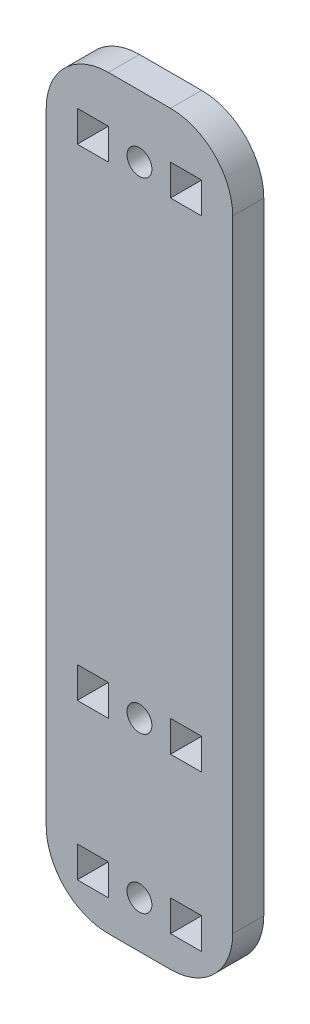
SolidWorks part; units mm, degrees
ref_plane "Plan de face" through (0, 0, 0) normal (0, 0, 1) x (1, 0, 0)
ref_plane "Plan de dessus" through (0, 0, 0) normal (0, 1, 0) x (1, 0, 0)
ref_plane "Plan de droite" through (0, 0, 0) normal (1, 0, 0) x (0, 0, -1)
sketch "Esquisse1" plane through (0, 0, 0) normal (0, 0, 1) x (1, 0, 0)
  line L0 (0, -120) -> (0, 0)
  line L1 (0, -120) -> (-30, -120)
  line L2 (0, 0) -> (-30, 0)
  line L3 (-20, -7.5) -> (-25, -7.5)
  line L4 (-5, -110) -> (-10, -110)
  line L5 (-5, -110) -> (-5, -115)
  line L6 (-5, -115) -> (-10, -115)
  line L7 (-10, -110) -> (-10, -115)
  line L8 (-20, -110) -> (-25, -110)
  line L9 (-20, -110) -> (-20, -115)
  line L10 (-20, -115) -> (-25, -115)
  line L11 (-25, -110) -> (-25, -115)
  line L12 (-20, -85) -> (-25, -85)
  line L13 (-20, -85) -> (-20, -90)
  line L14 (-20, -90) -> (-25, -90)
  line L15 (-25, -85) -> (-25, -90)
  line L16 (-5, -85) -> (-10, -85)
  line L17 (-5, -85) -> (-5, -90)
  line L18 (-30, -120) -> (-30, 0)
  line L19 (-20, -7.5) -> (-20, -12.5)
  line L20 (-20, -12.5) -> (-25, -12.5)
  line L21 (-25, -7.5) -> (-25, -12.5)
  line L22 (-5, -90) -> (-10, -90)
  line L23 (-5, -7.5) -> (-10, -7.5)
  line L24 (-5, -7.5) -> (-5, -12.5)
  line L25 (-5, -12.5) -> (-10, -12.5)
  line L26 (-10, -7.5) -> (-10, -12.5)
  line L27 (-10, -10) -> (-20, -10) construction
  line L32 (-10, -85) -> (-10, -90)
  line L54 (-10, -90) -> (-20, -110) construction
  line L55 (-10, -87.5) -> (-20, -87.5) construction
  line L56 (-10, -112.5) -> (-20, -112.5) construction
  circle A0 centre (-15, -10) radius 2
  circle A18 centre (-15, -100) radius 7.5 construction
  circle A19 centre (-15, -87.5) radius 2
  circle A20 centre (-15, -112.5) radius 2
  point P2 (-7.5, -115)
  dimension "D9" = 5
  dimension "D10" = 5
  dimension "D11" = 10
  dimension "D13" = 5
  dimension "D14" = 4
  dimension "D29" = 15
  dimension "D33" = 4
  dimension "D34" = 4
  dimension "D3" = 20
  dimension "D4" = 10
  dimension "D5" = 30
  dimension "D6" = 120
  dimension "D7" = 10
  dimension "D8" = 5
  dimension "D12" = 5
extrude "Boss.-Extru.1" add sketch "Esquisse1" along normal blind 5
fillet "Congé1" radius 10 4 edges at (-30, -120, 2.5) (0, -120, 2.5) (0, 0, 2.5) (-30, 0, 2.5)
